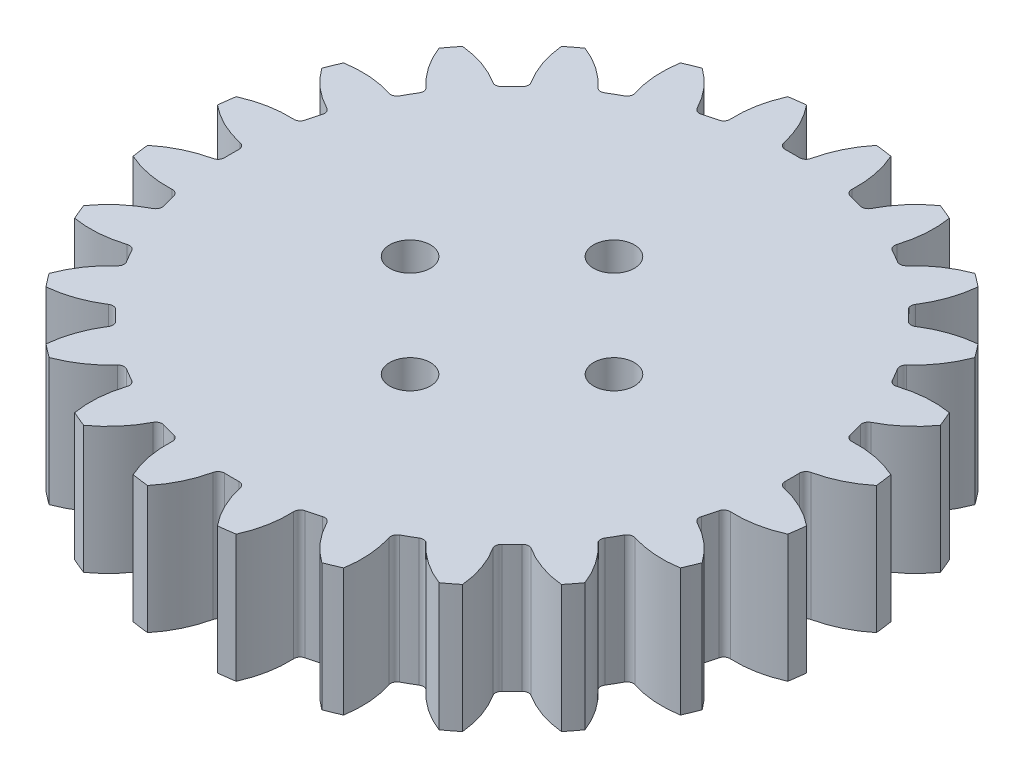
SolidWorks part; units mm, degrees
ref_plane "前视基准面" through (0, 0, 0) normal (0, 0, 1) x (1, 0, 0)
ref_plane "上视基准面" through (0, 0, 0) normal (0, 1, 0) x (1, 0, 0)
ref_plane "右视基准面" through (0, 0, 0) normal (1, 0, 0) x (0, 0, -1)
other "Configuration Table"
sketch "草图1" plane through (0, 0, 0) normal (0, 1, 0) x (1, 0, 0)
  circle A0 centre (0, 0) radius 26
  dimension "D1" = 52
extrude "凸台-拉伸1" add sketch "草图1" along normal blind 10
sketch "草图2" plane through (0, 0, 0) normal (0, 1, 0) x (1, 0, 0)
  line L0 (0, 32.5284) -> (0, -27.4432) construction
  line L1 (0, 0) -> (2.2127, 33.7594) construction
  line L2 (1.5697, 23.9486) -> (24.0107, 22.4778) construction
  line L3 (1.5697, 23.9486) -> (26.0747, 13.1661) construction
  line L4 (0, 0) -> (9.083, 20.6427) construction
  circle A0 centre (0, 0) radius 24 construction
  arc A1 (0.5605, 21.9929) -> (-0.5605, 21.9929) centre (0, 0) ccw
  arc A2 (2.7418, 25.855) -> (-2.7418, 25.855) centre (0, 0) ccw
  circle A3 centre (0, 0) radius 26 construction
  arc A4 (2.7418, 25.855) -> (1.0619, 22.3865) centre (9.083, 20.6427) ccw
  arc A5 (1.0619, 22.3865) -> (0.5605, 21.9929) centre (0.5733, 22.4927) cw
  arc A6 (-1.0619, 22.3865) -> (-0.5605, 21.9929) centre (-0.5733, 22.4927) ccw
  arc A7 (-2.7418, 25.855) -> (-1.0619, 22.3865) centre (-9.083, 20.6427) cw
  dimension "D2" = 48
  dimension "D4" = 22
  dimension "D5" = 0.5
  dimension "D1" = 3.75
  dimension "D3" = 20
extrude "切除-拉伸1" cut sketch "草图2" along normal through all
pattern_circular "阵列(圆周)1" count 24 over 360 about axis through (0, 0, 0) along (0, 1, 0) of "切除-拉伸1"
sketch "草图3" plane through (0, 0, 0) normal (0, 1, 0) x (1, 0, 0)
  circle A0 centre (0, 0) radius 8 construction
  circle A1 centre (0, 8) radius 1.6
  circle A2 centre (8, 0) radius 1.6
  circle A3 centre (0, -8) radius 1.6
  circle A4 centre (-8, 0) radius 1.6
  point P14 (0, 0)
  dimension "D1" = 16
  dimension "D2" = 3.2
  dimension "D3" = 4
extrude "切除-拉伸2" cut sketch "草图3" along normal through all
sketch "草图4" plane through (0, 0, 0) normal (0, 1, 0) x (1, 0, 0)
  circle A0 centre (0, 0) radius 24 construction
  dimension "D1" = 48
